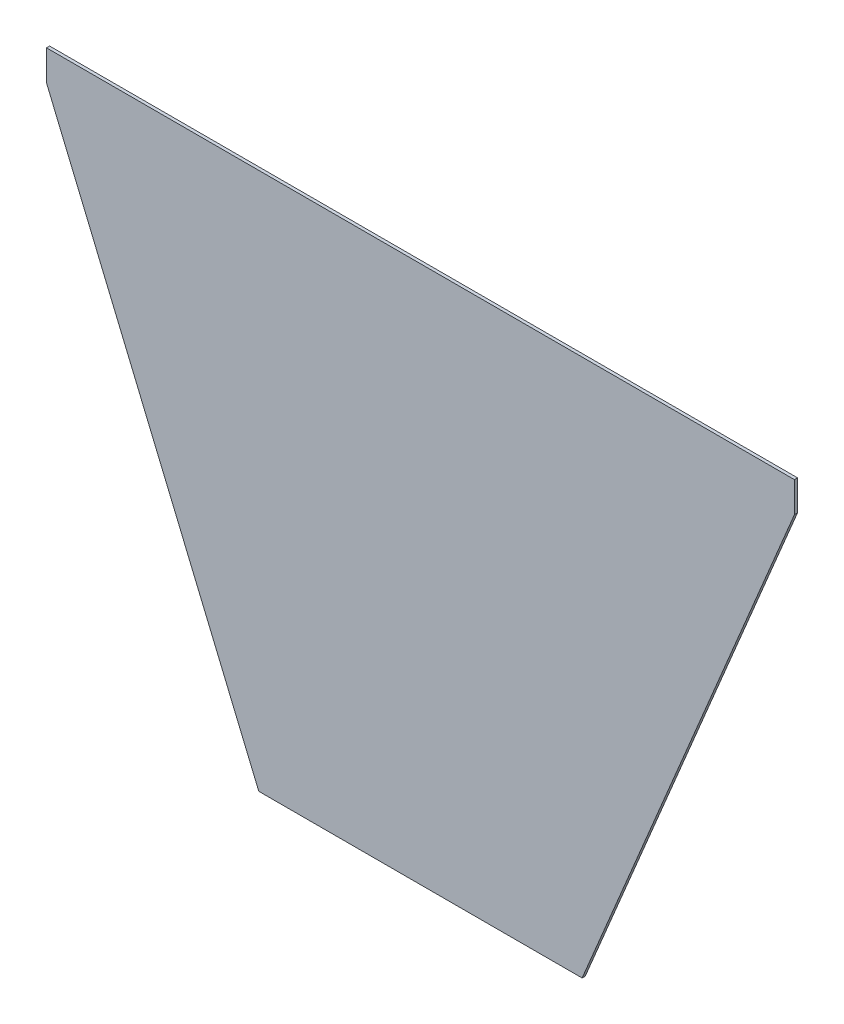
SolidWorks part; units mm, degrees
ref_plane "前视基准面" through (0, 0, 0) normal (0, 0, 1) x (1, 0, 0)
ref_plane "上视基准面" through (0, 0, 0) normal (0, 1, 0) x (1, 0, 0)
ref_plane "右视基准面" through (0, 0, 0) normal (1, 0, 0) x (0, 0, -1)
sketch "草图1" plane through (0, 0, 0) normal (0, 0, 1) x (1, 0, 0)
  line L0 (-603.605, 0) -> (603.605, 0)
  line L1 (-603.605, 0) -> (-603.605, -49)
  line L2 (-260.935, -868) -> (260.935, -868)
  line L3 (603.605, 0) -> (603.605, -49)
  line L4 (-603.605, -49) -> (-260.935, -868)
  line L5 (603.605, -49) -> (260.935, -868)
  line L6 (0, 244.6389) -> (0, -1227.8543) construction
  line L9 (-603.605, -868) -> (603.605, -868) construction
  dimension "D1" = 1207.21
  dimension "D3" = 49
  dimension "D4" = 49
  dimension "D5" = 521.87
  dimension "D2" = 868
extrude "凸台-拉伸1" add sketch "草图1" along normal blind 5
